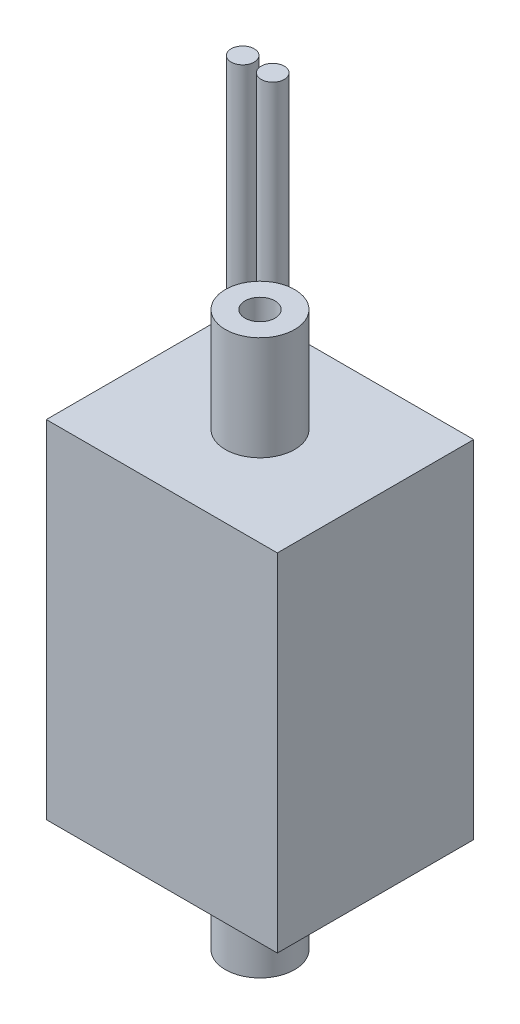
SolidWorks part; units mm, degrees
ref_plane "Plan de face" through (0, 0, 0) normal (0, 0, 1) x (1, 0, 0)
ref_plane "Plan de dessus" through (0, 0, 0) normal (0, 1, 0) x (1, 0, 0)
ref_plane "Plan de droite" through (0, 0, 0) normal (1, 0, 0) x (0, 0, -1)
sketch "Esquisse1" plane through (0, 0, 0) normal (0, 0, 1) x (1, 0, 0)
  line L1 (0, 0) -> (10, 0)
  line L2 (0, 0) -> (0, 15)
  line L3 (0, 15) -> (10, 15)
  line L4 (10, 0) -> (10, 15)
  dimension "D1" = 10
  dimension "D2" = 15
extrude "Boss.-Extru.1" add sketch "Esquisse1" along normal blind 8.5
sketch "Esquisse2" plane through (0, 0, 0) normal (0, -1, 0) x (1, 0, 0)
  line L0 (0, 0) -> (10, 8.5) construction
  circle A0 centre (5, 4.25) radius 1.5
  circle A1 centre (5, 4.25) radius 0.5
  dimension "D1" = 3
  dimension "D2" = 1
extrude "Boss.-Extru.2" add sketch "Esquisse2" along normal blind 4.5
sketch "Esquisse3" plane through (0, 15, 0) normal (0, 1, 0) x (1, 0, 0)
  line L0 (0, 0) -> (10, -8.5) construction
  circle A0 centre (5, -4.25) radius 1.5
  circle A1 centre (5, -4.25) radius 0.65
  dimension "D1" = 1.3
  dimension "D2" = 3
extrude "Boss.-Extru.3" add sketch "Esquisse3" along normal blind 4.5 separate body
sketch "Esquisse4" plane through (0, 15, 0) normal (0, 1, 0) x (1, 0, 0)
  line L0 (0.6, -0.6) -> (1.9, -0.6) construction
  line L1 (0, -8.5) -> (0, 0) construction
  line L2 (10, 0) -> (0, 0) construction
  circle A0 centre (0.6, -0.6) radius 0.5
  circle A1 centre (1.9, -0.6) radius 0.5
  dimension "D1" = 1
  dimension "D2" = 1.3
  dimension "D3" = 0.6
  dimension "D4" = 0.6
extrude "Boss.-Extru.4" add sketch "Esquisse4" along normal blind 10
equation "\"D4@Esquisse4\"=\"D3@Esquisse4\""
